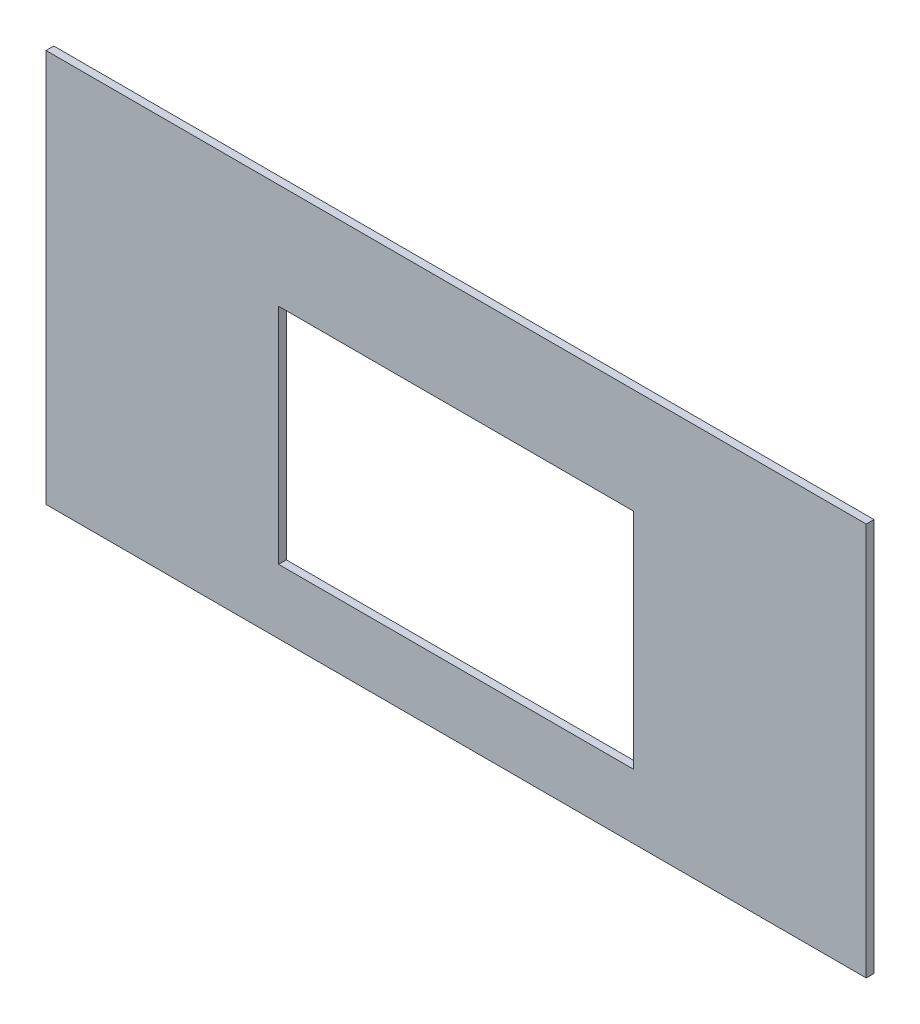
SolidWorks part; units mm, degrees
ref_plane "정면" through (0, 0, 0) normal (0, 0, 1) x (1, 0, 0)
ref_plane "윗면" through (0, 0, 0) normal (0, 1, 0) x (1, 0, 0)
ref_plane "우측면" through (0, 0, 0) normal (1, 0, 0) x (0, 0, -1)
sketch "Sketch1" plane through (0, 0, 0) normal (0, 0, 1) x (1, 0, 0)
  line L1 (-31.19, 14.95) -> (31.19, 14.95)
  line L2 (-31.19, 14.95) -> (-31.19, -14.95)
  line L3 (-31.19, -14.95) -> (31.19, -14.95)
  line L4 (31.19, 14.95) -> (31.19, -14.95)
  line L5 (-31.19, 14.95) -> (31.19, -14.95) construction
  line L6 (-31.19, -14.95) -> (31.19, 14.95) construction
  point P0 (0, 0)
  dimension "D1" = 62.38
  dimension "D2" = 29.9
extrude "Boss-Extrude1" add sketch "Sketch1" along normal blind 0.59
sketch "Sketch2" plane through (0, 0, 0.59) normal (0, 0, 1) x (1, 0, 0)
  line L0 (-31.19, 14.95) -> (31.19, -14.95) construction
  line L1 (31.19, 14.95) -> (-31.19, -14.95) construction
  line L2 (31.19, 14.95) -> (-31.19, 14.95) construction
  line L3 (-13.5, 6.95) -> (13.5, 6.95)
  line L4 (-13.5, 6.95) -> (-13.5, -10.05)
  line L5 (-13.5, -10.05) -> (13.5, -10.05)
  line L6 (13.5, 6.95) -> (13.5, -10.05)
  line L7 (-13.5, 6.95) -> (13.5, -10.05) construction
  line L8 (-13.5, -10.05) -> (13.5, 6.95) construction
  line L10 (0, 0) -> (0, 14.95) construction
  point P8 (0, 0)
  point P9 (0, 0)
  point P19 (0, 6.95)
  dimension "D1" = 8
  dimension "D2" = 17
  dimension "D3" = 27
extrude "Cut-Extrude1" cut sketch "Sketch2" against normal blind 1
